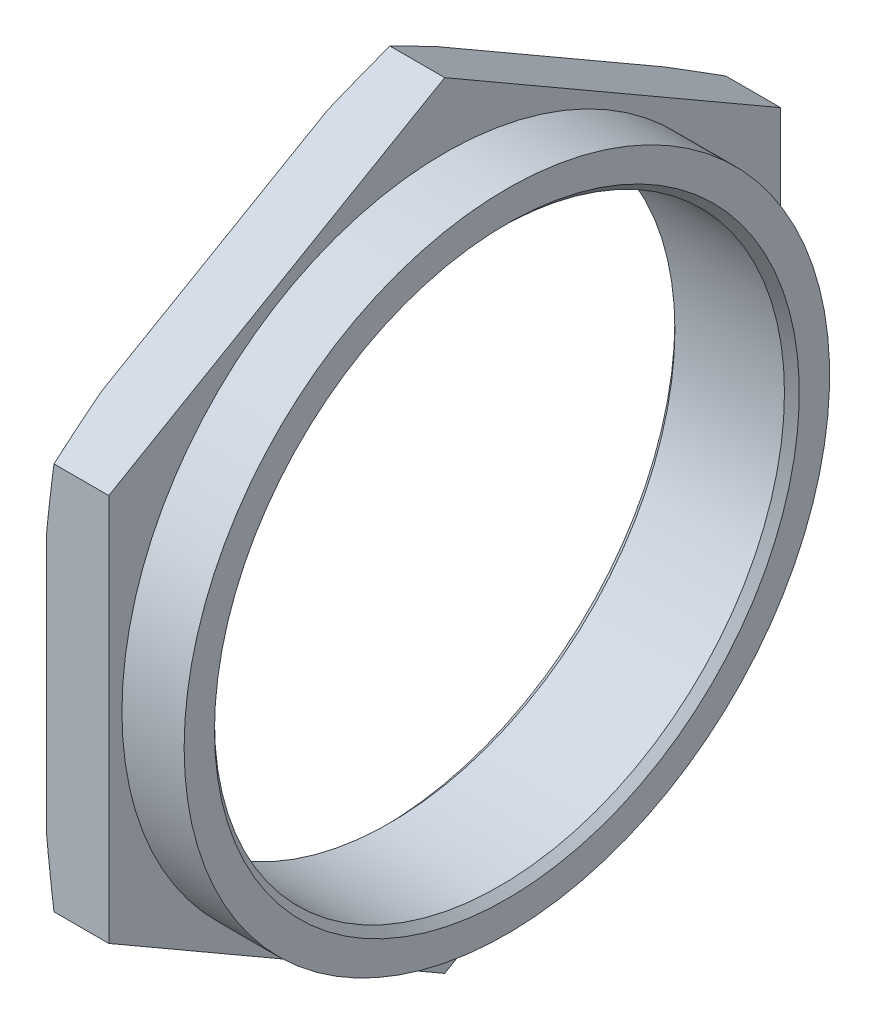
SolidWorks part; units mm, degrees
material "4140"
ref_plane "Front Plane" through (0, 0, 0) normal (0, 0, 1) x (1, 0, 0)
ref_plane "Top Plane" through (0, 0, 0) normal (0, 1, 0) x (1, 0, 0)
ref_plane "Right Plane" through (0, 0, 0) normal (1, 0, 0) x (0, 0, -1)
sketch "Sketch1" plane through (0, 0, 0) normal (0, 0, 1) x (1, 0, 0)
  line L0 (0, 0) -> (77.6492, 0) construction
  line L1 (0, 19.25) -> (0, 26.2)
  line L2 (0, 26.2) -> (4.2, 26.2)
  line L3 (4.2, 26.2) -> (4.2, 21.8)
  line L4 (4.2, 21.8) -> (8.4, 21.8)
  line L5 (8.4, 21.8) -> (8.4, 19.25)
  line L6 (8.4, 19.25) -> (0, 19.25)
  dimension "D1" = 52.4
  dimension "D2" = 43.6
  dimension "D3" = 8.4
  dimension "D4" = 4.2
  dimension "D5" = 38.5
revolve "Revolve1" add sketch "Sketch1" angle 360 about L0
cosmetic thread "Cosmetic Thread1" parameters "D2"=40
chamfer "Chamfer1" distance 0.5 angle 75 1 edges at (0, 0, 26.2)
sketch "Sketch2" plane through (0, 0, 0) normal (-1, 0, 0) x (0, 0, 1)
  line L1 (0, 26.2) -> (-22.6899, 13.1)
  line L2 (-22.6899, 13.1) -> (-22.6899, -13.1)
  line L3 (-22.6899, -13.1) -> (0, -26.2)
  line L4 (0, -26.2) -> (22.6899, -13.1)
  line L5 (22.6899, -13.1) -> (22.6899, 13.1)
  line L6 (22.6899, 13.1) -> (0, 26.2)
  circle A0 centre (0, 0) radius 22.6899 construction
  circle A1 centre (0, 0) radius 26.2 construction
  circle A2 centre (0, 0) radius 30.3503
  dimension "D1" = 60.7005
extrude "Extrude1" cut sketch "Sketch2" against normal through all
chamfer "Chamfer2" distance 0.5 angle 45 2 edges at (8.4, 0, 19.25) (0, 0, 19.25)
